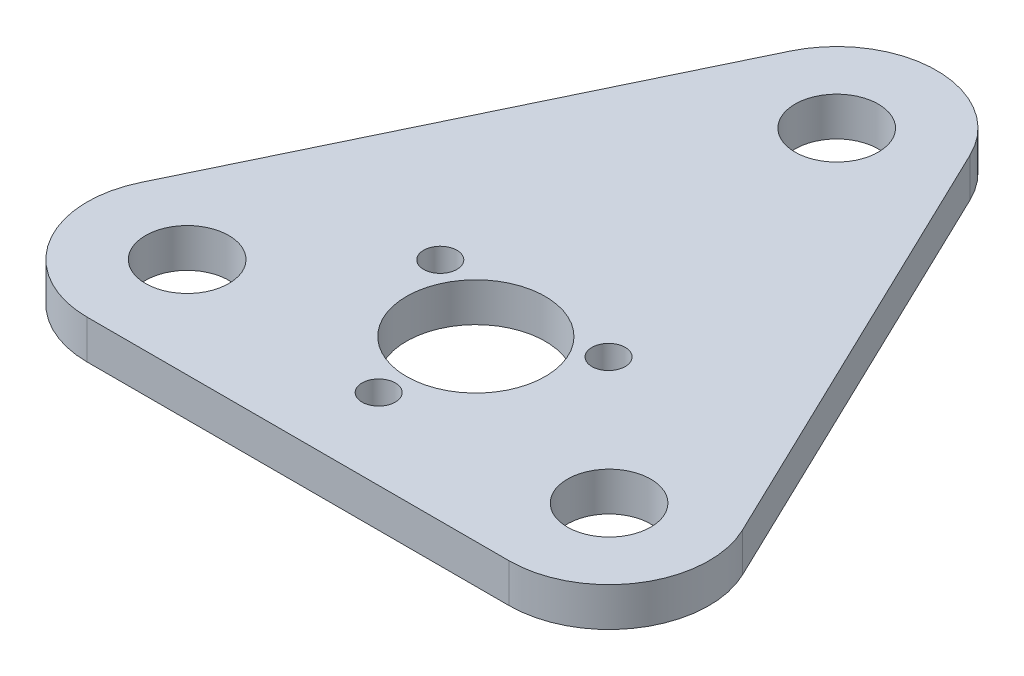
SolidWorks part; units mm, degrees
ref_plane "Front Plane" through (0, 0, 0) normal (0, 0, 1) x (1, 0, 0)
ref_plane "Top Plane" through (0, 0, 0) normal (0, 1, 0) x (1, 0, 0)
ref_plane "Right Plane" through (0, 0, 0) normal (1, 0, 0) x (0, 0, -1)
sketch "Sketch1" plane through (0, 0, 0) normal (0, 1, 0) x (1, 0, 0)
  line L0 (0, 0) -> (0, 110.906) construction
  line L1 (38, 0) -> (-38, 0) construction
  line L2 (-38, 0) -> (0, 79) construction
  line L3 (-54.221, 7.8025) -> (-16.221, 86.8025)
  line L4 (38, 0) -> (0, 79) construction
  line L5 (16.221, 86.8025) -> (54.221, 7.8025)
  line L6 (-38, -18) -> (38, -18)
  line L7 (-17.5, 14) -> (17.5, 14) construction
  line L8 (0, 14) -> (-15.1554, 22.75) construction
  line L9 (17.5, 14) -> (-17.5, 14) construction
  line L10 (0, 14) -> (15.1554, 22.75) construction
  circle A0 centre (-38, 0) radius 7.5
  circle A1 centre (0, 79) radius 7.5
  circle A2 centre (38, 0) radius 7.5
  arc A3 (16.221, 86.8025) -> (-16.221, 86.8025) centre (0, 79) ccw
  arc A4 (-54.221, 7.8025) -> (-38, -18) centre (-38, 0) ccw
  arc A5 (38, -18) -> (54.221, 7.8025) centre (38, 0) ccw
  circle A6 centre (0, 14) radius 12.5
  circle A7 centre (0, 14) radius 17.5 construction
  circle A8 centre (-15.1554, 22.75) radius 3
  circle A9 centre (15.1554, 22.75) radius 3
  circle A10 centre (0, -3.5) radius 3
  point P10 (0, 97)
  dimension "D1" = 15
  dimension "D2" = 36
  dimension "D5" = 25
  dimension "D8" = 35
  dimension "D9" = 6
  dimension "D3" = 115
  dimension "D4" = 76
  dimension "D6" = 32
  dimension "D7" = 30
extrude "Boss-Extrude1" add sketch "Sketch1" along normal mid plane 7
